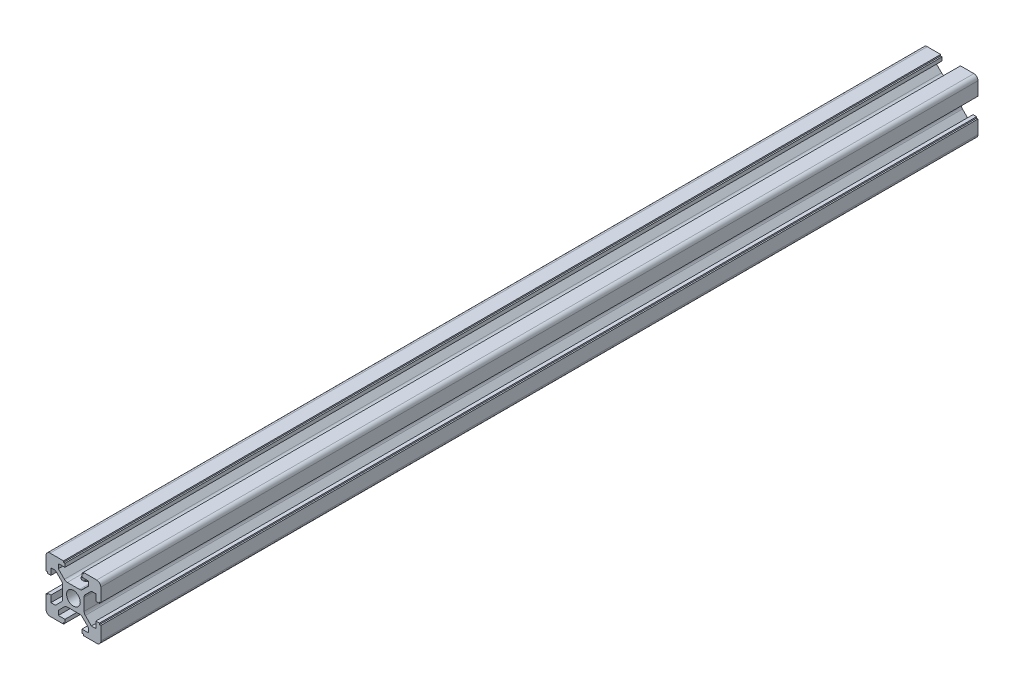
SolidWorks part; units mm, degrees
material "6061 合金"
ref_plane "前视基准面" through (0, 0, 0) normal (0, 0, 1) x (1, 0, 0)
ref_plane "上视基准面" through (0, 0, 0) normal (0, 1, 0) x (1, 0, 0)
ref_plane "右视基准面" through (0, 0, 0) normal (1, 0, 0) x (0, 0, -1)
sketch "草图1" plane through (0, 0, 0) normal (0, 0, 1) x (1, 0, 0)
  line L0 (-6.5607, 5.5) -> (-4.3393, 3.2787)
  line L1 (-3.9, 2.218) -> (-3.9, -2.218)
  line L2 (-4.3393, -3.2787) -> (-6.5607, -5.5)
  line L3 (-6.5607, -5.5) -> (-8.2, -5.5)
  line L4 (-8.2, -5.5) -> (-8.2, -3.1)
  line L5 (-8.2, -3.1) -> (-9.5, -3.1)
  line L6 (-9.5, -3.1) -> (-9.5, -3.6)
  line L7 (-9.5, -3.6) -> (-10, -3.6)
  line L8 (-10, -3.6) -> (-10, -8.5)
  line L9 (-6.5607, 5.5) -> (-8.2, 5.5)
  line L10 (-8.2, 5.5) -> (-8.2, 3.1)
  line L11 (-8.2, 3.1) -> (-9.5, 3.1)
  line L12 (-9.5, 3.1) -> (-9.5, 3.6)
  line L13 (-9.5, 3.6) -> (-10, 3.6)
  line L14 (-10, 3.6) -> (-10, 8.5)
  line L15 (5.5, 6.5607) -> (3.2787, 4.3393)
  line L16 (2.218, 3.9) -> (-2.218, 3.9)
  line L17 (-3.2787, 4.3393) -> (-5.5, 6.5607)
  line L18 (-5.5, 6.5607) -> (-5.5, 8.2)
  line L19 (-5.5, 8.2) -> (-3.1, 8.2)
  line L20 (-3.1, 8.2) -> (-3.1, 9.5)
  line L21 (-3.1, 9.5) -> (-3.6, 9.5)
  line L22 (-3.6, 9.5) -> (-3.6, 10)
  line L23 (-3.6, 10) -> (-8.5, 10)
  line L24 (5.5, 6.5607) -> (5.5, 8.2)
  line L25 (5.5, 8.2) -> (3.1, 8.2)
  line L26 (3.1, 8.2) -> (3.1, 9.5)
  line L27 (3.1, 9.5) -> (3.6, 9.5)
  line L28 (3.6, 9.5) -> (3.6, 10)
  line L29 (3.6, 10) -> (8.5, 10)
  line L30 (6.5607, -5.5) -> (4.3393, -3.2787)
  line L31 (3.9, -2.218) -> (3.9, 2.218)
  line L32 (4.3393, 3.2787) -> (6.5607, 5.5)
  line L33 (6.5607, 5.5) -> (8.2, 5.5)
  line L34 (8.2, 5.5) -> (8.2, 3.1)
  line L35 (8.2, 3.1) -> (9.5, 3.1)
  line L36 (9.5, 3.1) -> (9.5, 3.6)
  line L37 (9.5, 3.6) -> (10, 3.6)
  line L38 (10, 3.6) -> (10, 8.5)
  line L39 (6.5607, -5.5) -> (8.2, -5.5)
  line L40 (8.2, -5.5) -> (8.2, -3.1)
  line L41 (8.2, -3.1) -> (9.5, -3.1)
  line L42 (9.5, -3.1) -> (9.5, -3.6)
  line L43 (9.5, -3.6) -> (10, -3.6)
  line L44 (10, -3.6) -> (10, -8.5)
  line L45 (-5.5, -6.5607) -> (-3.2787, -4.3393)
  line L46 (-2.218, -3.9) -> (2.218, -3.9)
  line L47 (3.2787, -4.3393) -> (5.5, -6.5607)
  line L48 (5.5, -6.5607) -> (5.5, -8.2)
  line L49 (5.5, -8.2) -> (3.1, -8.2)
  line L50 (3.1, -8.2) -> (3.1, -9.5)
  line L51 (3.1, -9.5) -> (3.6, -9.5)
  line L52 (3.6, -9.5) -> (3.6, -10)
  line L53 (3.6, -10) -> (8.5, -10)
  line L54 (-5.5, -6.5607) -> (-5.5, -8.2)
  line L55 (-5.5, -8.2) -> (-3.1, -8.2)
  line L56 (-3.1, -8.2) -> (-3.1, -9.5)
  line L57 (-3.1, -9.5) -> (-3.6, -9.5)
  line L58 (-3.6, -9.5) -> (-3.6, -10)
  line L59 (-3.6, -10) -> (-8.5, -10)
  line L60 (0, 0) -> (-3.9, 2.8393) construction
  line L61 (0, 0) -> (2.8393, 3.9) construction
  arc A0 (4.3393, -3.2787) -> (3.9, -2.218) centre (5.4, -2.218) cw
  arc A1 (3.9, 2.218) -> (4.3393, 3.2787) centre (5.4, 2.218) cw
  arc A2 (3.2787, 4.3393) -> (2.218, 3.9) centre (2.218, 5.4) cw
  arc A3 (-2.218, 3.9) -> (-3.2787, 4.3393) centre (-2.218, 5.4) cw
  arc A4 (-4.3393, 3.2787) -> (-3.9, 2.218) centre (-5.4, 2.218) cw
  arc A5 (-3.9, -2.218) -> (-4.3393, -3.2787) centre (-5.4, -2.218) cw
  arc A6 (2.218, -3.9) -> (3.2787, -4.3393) centre (2.218, -5.4) cw
  arc A7 (-3.2787, -4.3393) -> (-2.218, -3.9) centre (-2.218, -5.4) cw
  arc A8 (-10, -8.5) -> (-8.5, -10) centre (-8.5, -8.5) ccw
  arc A9 (10, -8.5) -> (8.5, -10) centre (8.5, -8.5) cw
  arc A10 (8.5, 10) -> (10, 8.5) centre (8.5, 8.5) cw
  arc A11 (-10, 8.5) -> (-8.5, 10) centre (-8.5, 8.5) cw
  circle A12 centre (0, 0) radius 2.5
  point P27 (-3.9, 0)
  point P75 (2.8393, 3.9)
  dimension "D12" = 1.5
  dimension "D13" = 5
  dimension "D2" = 20
  dimension "D3" = 7.2
  dimension "D4" = 6.2
  dimension "D5" = 7.8
  dimension "D6" = 45
  dimension "D7" = 1.5
  dimension "D8" = 11
  dimension "D9" = 1.8
  dimension "D10" = 0.5
  dimension "D11" = 3.1
  dimension "D1" = 4
extrude "凸台-拉伸1" add sketch "草图1" along normal mid plane 320
sketch "草图3" plane through (0, 10, 0) normal (0, 1, 0) x (1, 0, 0)
  line L0 (2.218, 160) -> (-2.218, 160) construction
  line L1 (-3.6, -160) -> (-8.5, -160) construction
  circle A0 centre (0, 155) radius 1.6
  circle A2 centre (0, 140) radius 1.6
  circle A3 centre (0, -155) radius 1.6
  circle A4 centre (0, -140) radius 1.6
  point P2 (0, 0)
  point P5 (0, 0)
  point P8 (0, 0)
  point P9 (0, 0)
  point P11 (0, 0)
  point P14 (0, 230)
  point P17 (18.8205, 238.4771)
  point P18 (0, 0)
  point P19 (18.7283, 216.3201)
  point P20 (0, 0)
  point P21 (0, 83.9637)
  point P22 (13.8748, 102.2602)
  point P25 (0, 0)
  point P26 (0, 0)
  dimension "D1" = 3.2
  dimension "D2" = 15
  dimension "D3" = 5
  dimension "D4" = 15
  dimension "D5" = 5
extrude "切除-拉伸1" cut sketch "草图3" against normal through all
